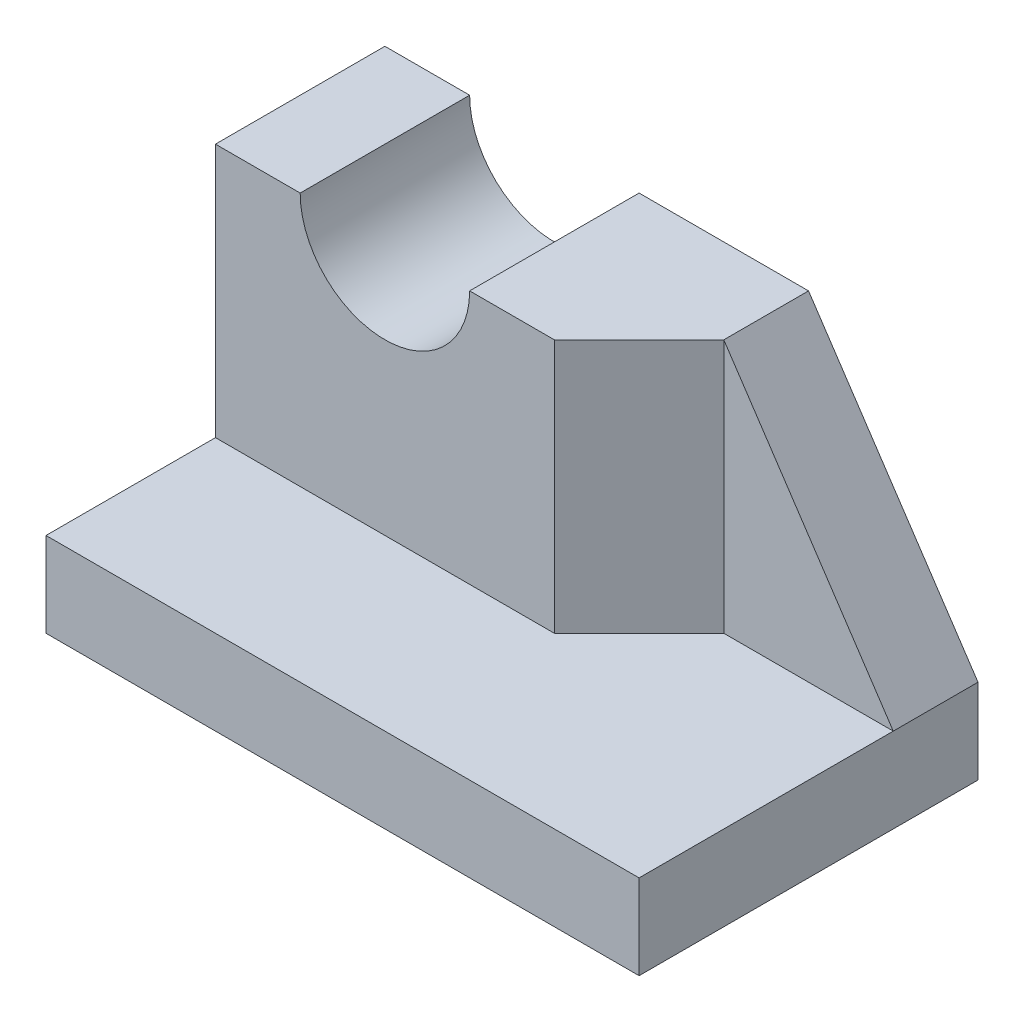
SolidWorks part; units mm, degrees
ref_plane "前基準面" through (0, 0, 0) normal (0, 0, 1) x (1, 0, 0)
ref_plane "上基準面" through (0, 0, 0) normal (0, 1, 0) x (1, 0, 0)
ref_plane "右基準面" through (0, 0, 0) normal (1, 0, 0) x (0, 0, -1)
sketch "草圖1" plane through (0, 0, 0) normal (0, 0, 1) x (1, 0, 0)
  line L0 (25, 20) -> (35, 5)
  line L1 (0, 0) -> (35, 0)
  line L2 (0, 0) -> (0, 20)
  line L3 (0, 20) -> (25, 20)
  line L4 (35, 0) -> (35, 5)
  dimension "D1" = 5
  dimension "D2" = 35
  dimension "D3" = 25
  dimension "D4" = 20
extrude "填料-伸長1" add sketch "草圖1" along normal blind 20
ref_plane "平面1" through (0, 5, 0) normal (0, -1, 0) x (-1, 0, 0)
sketch "草圖2" plane through (0, 5, 0) normal (0, -1, 0) x (-1, 0, 0)
  line L0 (-35, 0) -> (-25, 0) construction
  line L1 (-25, 0) -> (0, 0) construction
  line L2 (-35, 0) -> (-25, 0)
  line L3 (-25, 0) -> (0, 0)
  line L4 (-35, 0) -> (-35, -5)
  line L5 (-35, -20) -> (-35, 0) construction
  line L6 (-35, -5) -> (-25, -5)
  line L7 (-25, -5) -> (-20, -10)
  line L8 (-20, -10) -> (0, -10)
  line L9 (0, -20) -> (0, 0) construction
  line L10 (0, -10) -> (0, 0)
  point P13 (-25.5842, -5)
  dimension "D1" = 10
  dimension "D2" = 5
  dimension "D3" = 5
  dimension "D4" = 10
  dimension "D5" = 5
  dimension "D6" = 5
extrude "除料-伸長1" cut sketch "草圖2" against normal blind 20 flip side to cut
sketch "草圖4" plane through (0, 0, 10) normal (0, 0, 1) x (1, 0, 0)
  line L0 (20, 20) -> (0, 20) construction
  line L1 (0, 20) -> (0, 5) construction
  circle A0 centre (10, 20) radius 5
  dimension "D1" = 10
  dimension "D2" = 10
extrude "除料-伸長2" cut sketch "草圖4" against normal through all
